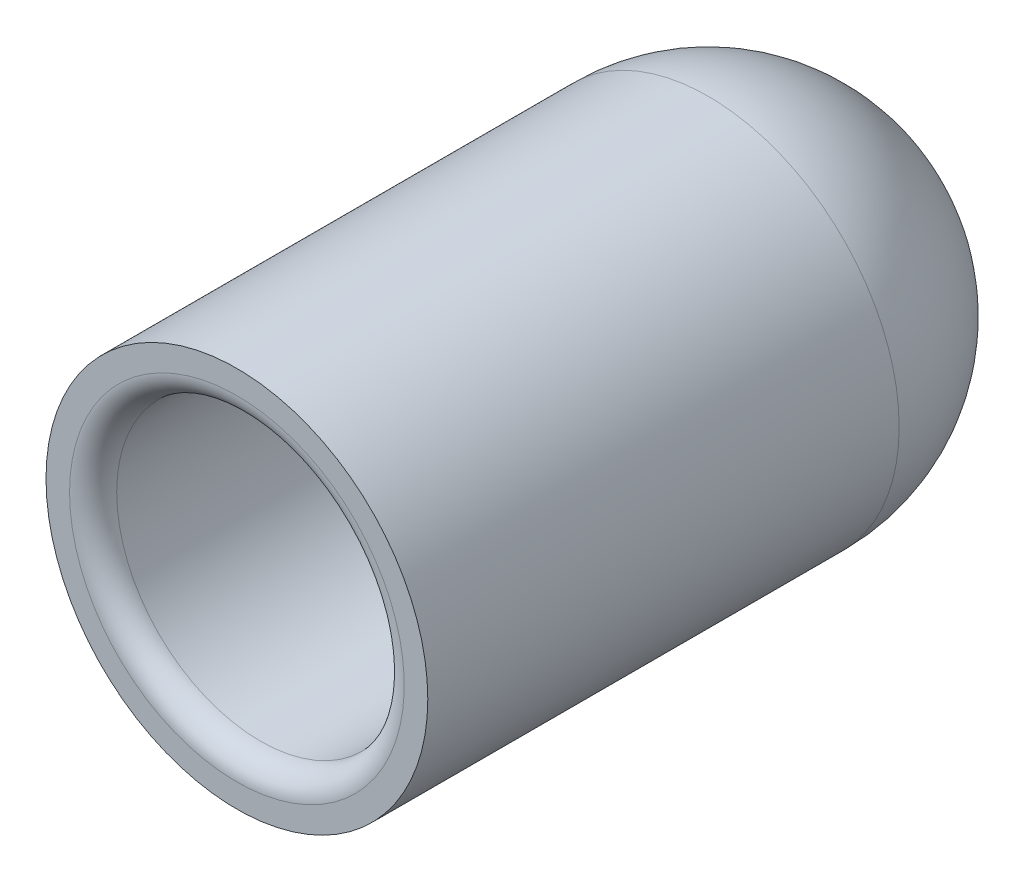
SolidWorks part; units mm, degrees
ref_plane "Front Plane" through (0, 0, 0) normal (0, 0, 1) x (1, 0, 0)
ref_plane "Top Plane" through (0, 0, 0) normal (0, 1, 0) x (1, 0, 0)
ref_plane "Right Plane" through (0, 0, 0) normal (1, 0, 0) x (0, 0, -1)
sketch "Sketch1" plane through (0, 0, 0) normal (0, 1, 0) x (1, 0, 0)
  line L0 (0, 0) -> (-6.1, 0)
  line L1 (-6.1, 0) -> (-6.1, 20)
  line L2 (-6.1, 20) -> (0, 20)
  line L3 (-8.1, 20) -> (-8.1, 0)
  line L4 (-8.1, 0) -> (-6.1, 0)
  line L5 (0, 0) -> (0, 28.1)
  circle A2 centre (0, 20) radius 6.1
  circle A3 centre (0, 20) radius 8.1
  dimension "D1" = 6.1
revolve "Revolve1" add sketch "Sketch1" angle 360 about L5
fillet "Fillet1" radius 1 1 edges at (6.1, 0, 0)
